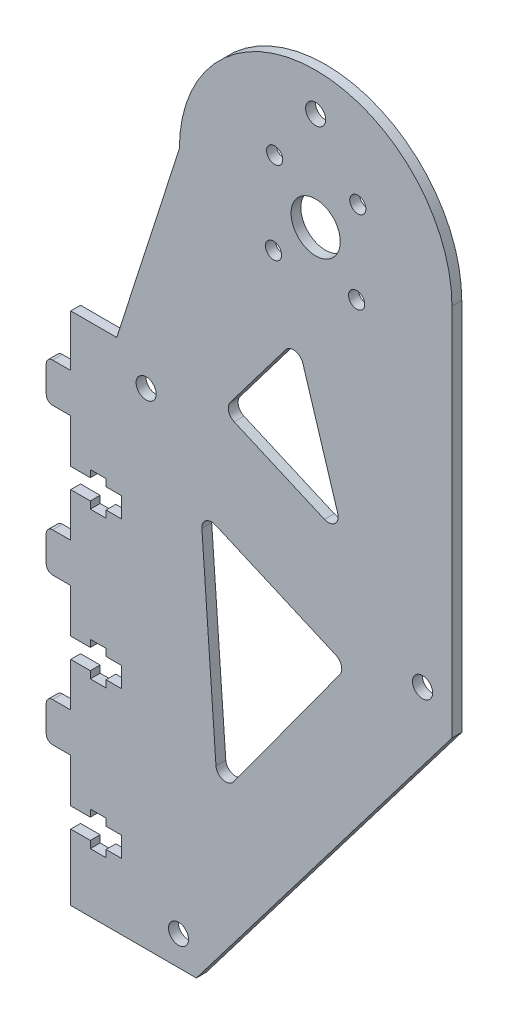
SolidWorks part; units mm, degrees
ref_plane "前视基准面" through (0, 0, 0) normal (0, 0, 1) x (1, 0, 0)
ref_plane "上视基准面" through (0, 0, 0) normal (0, 1, 0) x (1, 0, 0)
ref_plane "右视基准面" through (0, 0, 0) normal (1, 0, 0) x (0, 0, -1)
sketch "草图1" plane through (0, 0, 0) normal (0, 0, 1) x (1, 0, 0)
  line L4 (298.5456, -83.8944) -> (298.5456, -92.8418)
  line L11 (348.537, 4.3962) -> (298.542, 5.1056) construction
  line L15 (298.5456, -96.9418) -> (302.5456, -96.9418)
  line L16 (302.5456, -96.9418) -> (302.5456, -98.3918)
  line L17 (302.5456, -98.3918) -> (305.7456, -98.3918)
  line L18 (305.7456, -98.3918) -> (305.7456, -96.9418)
  line L19 (305.7456, -96.9418) -> (308.9456, -96.9418)
  line L20 (308.9456, -96.9418) -> (308.9456, -92.8418)
  line L21 (308.9456, -92.8418) -> (305.7456, -92.8418)
  line L22 (305.7456, -92.8418) -> (305.7456, -91.3918)
  line L23 (305.7456, -91.3918) -> (302.5456, -91.3918)
  line L24 (302.5456, -91.3918) -> (302.5456, -92.8418)
  line L25 (302.5456, -92.8418) -> (298.5456, -92.8418)
  line L27 (298.5456, -94.8944) -> (302.5431, -94.8944) construction
  line L28 (298.5456, -109.8944) -> (303.5456, -109.8944) construction
  line L29 (303.5456, -113.8944) -> (293.5456, -113.8944) construction
  line L30 (303.5456, -113.8944) -> (303.5456, -105.8944) construction
  line L31 (303.5456, -105.8944) -> (293.5456, -105.8944) construction
  line L32 (293.5456, -113.8944) -> (293.5456, -105.8944)
  line L33 (303.5456, -113.8944) -> (293.5456, -105.8944) construction
  line L34 (303.5456, -105.8944) -> (293.5456, -113.8944) construction
  line L35 (302.5456, -126.947) -> (298.5456, -126.947)
  line L36 (298.5456, -122.847) -> (302.5456, -122.847)
  line L37 (302.5456, -128.397) -> (302.5456, -126.947)
  line L38 (305.7456, -128.397) -> (302.5456, -128.397)
  line L39 (305.7456, -126.947) -> (305.7456, -128.397)
  line L40 (308.9456, -126.947) -> (305.7456, -126.947)
  line L41 (308.9456, -122.847) -> (308.9456, -126.947)
  line L42 (305.7456, -122.847) -> (308.9456, -122.847)
  line L43 (305.7456, -121.397) -> (305.7456, -122.847)
  line L44 (302.5456, -121.397) -> (305.7456, -121.397)
  line L45 (302.5456, -122.847) -> (302.5456, -121.397)
  line L46 (293.5456, -75.8944) -> (293.5456, -83.8944)
  line L47 (302.5456, -62.8418) -> (298.5456, -62.8418)
  line L48 (298.5456, -66.9418) -> (302.5456, -66.9418)
  line L49 (302.5456, -66.9418) -> (302.5456, -68.3918)
  line L50 (302.5456, -68.3918) -> (305.7456, -68.3918)
  line L51 (305.7456, -68.3918) -> (305.7456, -66.9418)
  line L52 (305.7456, -66.9418) -> (308.9456, -66.9418)
  line L53 (308.9456, -66.9418) -> (308.9456, -62.8418)
  line L54 (308.9456, -62.8418) -> (305.7456, -62.8418)
  line L55 (305.7456, -62.8418) -> (305.7456, -61.3918)
  line L56 (305.7456, -61.3918) -> (302.5456, -61.3918)
  line L57 (302.5456, -61.3918) -> (302.5456, -62.8418)
  line L58 (293.5456, -83.8944) -> (298.5456, -83.8944)
  line L59 (293.5456, -75.8944) -> (298.5456, -75.8944)
  line L60 (298.5456, -75.8944) -> (298.5456, -66.9418)
  line L63 (298.5456, -105.8944) -> (293.5456, -105.8944)
  line L64 (293.5456, -113.8944) -> (298.5456, -113.8944)
  line L65 (298.5456, -113.8944) -> (298.5456, -122.847)
  line L66 (308.9456, -64.8918) -> (305.2429, -64.8918) construction
  line L67 (293.5456, -45.8892) -> (298.5456, -45.8892)
  line L68 (293.5456, -53.8892) -> (293.5456, -45.8892)
  line L69 (293.5456, -53.8892) -> (298.5456, -53.8892)
  line L70 (298.5456, -53.8892) -> (298.5456, -62.8418)
  line L78 (298.5456, -126.947) -> (298.5456, -140.447)
  line L79 (298.5456, -140.447) -> (324.1889, -140.447)
  line L81 (376.3586, 4.3962) -> (376.3586, -71.947)
  line L84 (376.3586, -71.947) -> (324.1889, -140.447)
  line L85 (298.5456, -45.8892) -> (298.5456, -35.347)
  line L87 (298.5456, -35.347) -> (307.937, -35.347)
  line L88 (307.937, -35.347) -> (320.7154, 4.3962)
  line L89 (320.5456, -134.447) -> (313.937, -41.347) construction
  line L90 (313.937, -41.347) -> (370.3586, -65.947) construction
  line L91 (370.3586, -65.947) -> (320.5456, -134.447) construction
  line L92 (354.9473, -70.1368) -> (328.5796, -106.3961)
  line L93 (328.5796, -106.3961) -> (325.0814, -57.1152)
  line L94 (325.0814, -57.1152) -> (354.9473, -70.1368)
  line L95 (370.3586, -65.947) -> (348.537, 4.3962) construction
  line L96 (348.537, 4.3962) -> (313.937, -41.347) construction
  line L97 (329.5711, -37.2544) -> (354.3373, -48.0525)
  line L98 (354.3373, -48.0525) -> (344.7587, -17.1754)
  line L99 (344.7587, -17.1754) -> (329.5711, -37.2544)
  line L100 (348.537, 4.3962) -> (337.1349, 16.1265) construction
  line L101 (298.5456, -96.9418) -> (298.5456, -105.8944)
  line L104 (376.3586, -71.947) -> (376.3586, -11.3546) construction
  circle A11 centre (348.537, 4.3962) radius 5.0225
  circle A14 centre (348.537, 4.3962) radius 27.8216 construction
  circle A23 centre (348.5373, 24.4573) radius 2.05
  circle A24 centre (320.5456, -134.447) radius 2.05
  circle A25 centre (370.3586, -65.947) radius 2.05
  circle A26 centre (313.937, -41.347) radius 2.05
  circle A27 centre (348.537, 4.3962) radius 12 construction
  circle A28 centre (340.173, 13.001) radius 1.65
  arc A39 (320.7154, 4.3962) -> (376.3586, 4.3962) centre (348.537, 4.3962) cw
  circle A43 centre (357.1418, 12.7602) radius 1.65
  circle A44 centre (356.901, -4.2086) radius 1.65
  circle A45 centre (339.9322, -3.9678) radius 1.65
  point P20 (300.5444, -94.8944)
  point P30 (298.5456, -109.8944)
  dimension "D3" = 4.1
  dimension "D4" = 10.045
  dimension "D5" = 3.2
  dimension "D6" = 50
  dimension "D15" = 22
  dimension "D17" = 6
  dimension "D19" = 6
  dimension "D23" = 24
  dimension "D25" = 3.3
  dimension "D7" = 4
  dimension "D8" = 4
  dimension "D9" = 2.0526
  dimension "D10" = 15
  dimension "D11" = 8
  dimension "D12" = 10
  dimension "D13" = 100
  dimension "D14" = 13.5
  dimension "D16" = 6
  dimension "D18" = 6
  dimension "D20" = 6
  dimension "D24" = 45
  dimension "D30" = 7
  dimension "D21" = 10
  dimension "D22" = 10
extrude "凸台-拉伸1" add sketch "草图1" along normal blind 2
sketch "草图2" plane through (298.5456, 0, 0) normal (-1, 0, 0) x (0, 0, 1)
  line L0 (1, -66.9418) -> (1, -62.8418)
  line L1 (2, -66.9418) -> (0, -66.9418) construction
  line L2 (2, -62.8418) -> (0, -62.8418) construction
  circle A0 centre (1, -64.8918) radius 2.05
fillet "圆角1" radius 2 6 edges at (344.7587, -17.1754, 1) (329.5711, -37.2544, 1) (354.3373, -48.0525, 1) (325.0814, -57.1152, 1) (328.5796, -106.3961, 1) (354.9473, -70.1368, 1)
fillet "圆角2" radius 1.3 6 edges at (293.5456, -45.8892, 1) (293.5456, -53.8892, 1) (293.5456, -83.8944, 1) (293.5456, -75.8944, 1) (293.5456, -113.8944, 1) (293.5456, -105.8944, 1)
